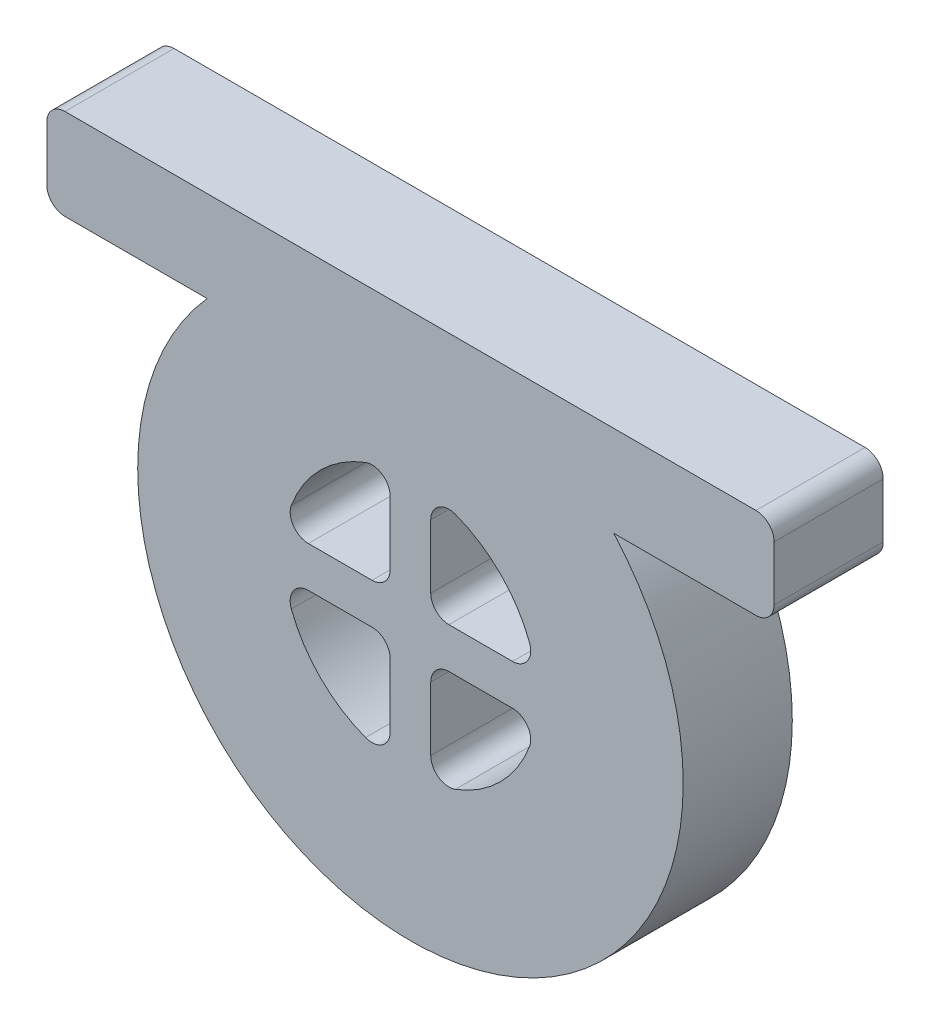
SolidWorks part; units mm, degrees
ref_plane "Front Plane" through (0, 0, 0) normal (0, 0, 1) x (1, 0, 0)
ref_plane "Top Plane" through (0, 0, 0) normal (0, 1, 0) x (1, 0, 0)
ref_plane "Right Plane" through (0, 0, 0) normal (1, 0, 0) x (0, 0, -1)
sketch "Sketch2" plane through (0, 0, 0) normal (0, 0, 1) x (1, 0, 0)
  line L0 (-69.5423, 39.9693) -> (-38.4188, 39.9693) construction
  line L1 (-53.3828, 53.823) -> (-53.3828, 24.0368) construction
  line L2 (-60.2932, 41.0855) -> (-54.4989, 41.0855)
  line L3 (-56.9591, 41.0855) -> (-56.9591, 39.9693) construction
  line L4 (-53.3828, 41.9209) -> (-54.4989, 41.9209) construction
  line L5 (-54.4989, 46.8798) -> (-54.4989, 41.0855)
  line L6 (-60.2932, 38.8532) -> (-54.4989, 38.8532)
  line L7 (-52.2666, 46.8798) -> (-52.2666, 41.0855)
  line L8 (-52.2666, 41.0855) -> (-46.4723, 41.0855)
  line L9 (-54.4989, 38.8532) -> (-54.4989, 33.0589)
  line L10 (-52.2666, 38.8532) -> (-46.4723, 38.8532)
  line L11 (-52.2666, 38.8532) -> (-52.2666, 33.0589)
  line L12 (-33.3828, 54.9693) -> (-73.3828, 54.9693)
  line L13 (-73.3828, 54.9693) -> (-73.3828, 49.9693)
  line L14 (-73.3828, 49.9693) -> (-33.3828, 49.9693)
  line L15 (-33.3828, 54.9693) -> (-33.3828, 49.9693)
  circle A0 centre (-53.3828, 39.9693) radius 10
  arc A1 (-54.4989, 46.8798) -> (-60.2932, 41.0855) centre (-53.3828, 39.9693) ccw
  arc A2 (-46.4723, 41.0855) -> (-52.2666, 46.8798) centre (-53.3828, 39.9693) ccw
  circle A3 centre (-53.3828, 39.9693) radius 7 construction
  arc A4 (-60.2932, 38.8532) -> (-54.4989, 33.0589) centre (-53.3828, 39.9693) ccw
  arc A5 (-52.2666, 33.0589) -> (-46.4723, 38.8532) centre (-53.3828, 39.9693) ccw
  arc A6 (-64.5631, 49.9693) -> (-42.2024, 49.9693) centre (-53.3828, 39.9693) ccw
  point P20 (-46.3828, 39.9693)
  point P31 (-53.3828, 49.9693)
  point P32 (-53.3828, 54.9693)
  dimension "D1" = 3
extrude "Boss-Extrude2" add sketch "Sketch2" along normal blind 6 contours L14 A6 A0 | L15 L12 L13 L14 | A0 A5 L11 L10 A4 L6 L9 A2 L8 L7 A1 L5 L2
fillet "Fillet1" radius 1 10 edges at (-52.2666, 33.0589, 3) (-46.4723, 38.8532, 3) (-54.4989, 33.0589, 3) (-60.2932, 38.8532, 3) (-60.2932, 41.0855, 3) (-54.4989, 41.0855, 3) (-54.4989, 46.8798, 3) (-52.2666, 46.8798, 3) (-46.4723, 41.0855, 3) (-52.2666, 41.0855, 3)
fillet "Fillet2" radius 1 2 edges at (-54.4989, 38.8532, 3) (-52.2666, 38.8532, 3)
fillet "Fillet3" radius 1 4 edges at (-73.3828, 54.9693, 3) (-73.3828, 49.9693, 3) (-33.3828, 54.9693, 3) (-33.3828, 49.9693, 3)
